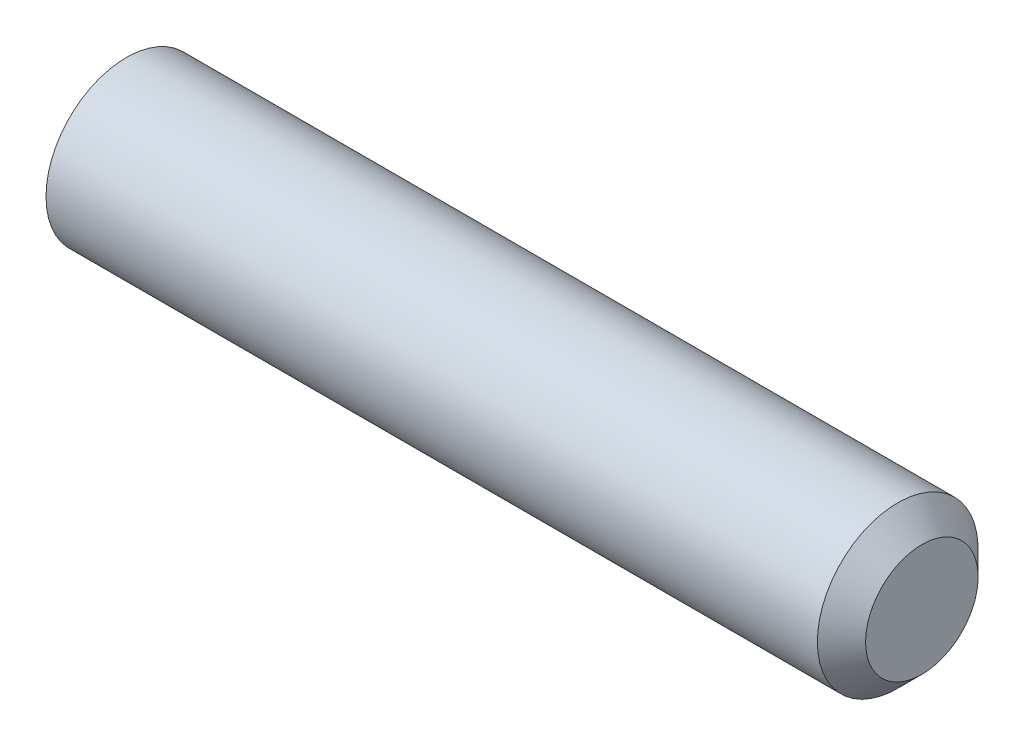
SolidWorks part; units mm, degrees
ref_plane "Plane1" through (0, 0, 0) normal (0, 0, 1) x (1, 0, 0)
ref_plane "Plane2" through (0, 0, 0) normal (0, 1, 0) x (1, 0, 0)
ref_plane "Plane3" through (0, 0, 0) normal (1, 0, 0) x (0, 0, -1)
sketch "BodySke" plane through (0, 0, 0) normal (0, 0, 1) x (1, 0, 0)
  line L0 (0, 0) -> (0, 2.055)
  line L1 (0, 2.055) -> (0.2569, 2.5)
  line L2 (0.2569, 2.5) -> (24.25, 2.5)
  line L3 (24.25, 2.5) -> (25, 1.75)
  line L4 (25, 0) -> (0, 0)
  line L5 (-12.7, 0) -> (88.9, 0) construction
  line L6 (25, 1.75) -> (25, 0)
  line L7 (25, 1.75) -> (25, 11.275) construction
  line L8 (0, -2.055) -> (0.2569, -2.5) construction
  line L9 (0.8, 15.875) -> (0.8, -3.175) construction
  line L10 (24.25, -2.5) -> (25, -1.75) construction
  dimension "Length" = 25
  dimension "Diameter" = 5
  dimension "Drive_ch_ang" = 60
  dimension "Minor_dia" = 4.11
  dimension "Cup_nose_ang" = 45
  dimension "Cup_dia" = 3.5
  dimension "Advance" = 0.8
revolve "BaseBody" add sketch "BodySke" angle 360 about L5
cosmetic thread "ThreadCosmetic" parameters "Thread_minor"=4.11
sketch "ThdSchSke" plane through (0, 0, 0) normal (0, 0, 1) x (1, 0, 0)
  line L0 (0.2569, -2.055) -> (-0.0547, -2.5)
  line L1 (0.2569, -2.055) -> (0.5685, -2.5)
  line L2 (0.5685, -2.5) -> (0.5685, -3.125)
  line L3 (-3.175, 0) -> (5.1513, 0) construction
  line L5 (0.5685, -3.125) -> (-0.0547, -3.125)
  line L6 (-0.0547, -3.125) -> (-0.0547, -2.5)
  line L8 (0.2569, 2.5) -> (0.2569, -2.5) construction
  dimension "Thread_minor" = 4.11
  dimension "Diameter" = 5
  dimension "SideAngle" = 55
  dimension "VeeAngle" = 70
  dimension "Overcut" = 6.25
revolve "ThreadSchematic" [suppressed] cut sketch "ThdSchSke" angle 360 about L3
pattern_linear "ThdSchPat" [suppressed]
equation "\"Thread_minor@ThreadCosmetic\" = \"Minor_dia@BodySke\""
equation "\"Thread_minor@ThdSchSke\" = \"Thread_minor@ThreadCosmetic\""
equation "\"Diameter@ThdSchSke\" = \"Diameter@BodySke\""
equation "\"Overcut@ThdSchSke\" = \"Diameter@BodySke\" * 1.25"
equation "\"Num_threads@ThdSchPat\" = int( (\"Length@BodySke\" - ( ( ( \"Diameter@BodySke\" - \"Minor_dia@BodySke\" ) * 0.5 ) / tan( \"Drive_ch_ang@BodySke\" * 0.017453292 ) ) - ( ( ( \"Diameter@BodySke\" - \"Cup_dia@BodySke\" ) * 0.5 ) * tan( \"Cup_nose_ang@BodySke\" * 0.017453292 ) ) ) / \"Advance@BodySke\" + 0.999 )  + 1"
equation "\"Advance@ThdSchPat\" = (\"Length@BodySke\" - ( ( ( \"Diameter@BodySke\" - \"Minor_dia@BodySke\" ) * 0.5 ) / tan( \"Drive_ch_ang@BodySke\" * 0.017453292 ) ) - ( ( ( \"Diameter@BodySke\" - \"Cup_dia@BodySke\" ) * 0.5 ) * tan( \"Cup_nose_ang@BodySke\" * 0.017453292 ) ) ) /  (\"Num_threads@ThdSchPat\" - 1) 'relax it"
equation "' \"Num_threads@ThdSchPat\" = \"Num_threads@ThdSchPat\" - sgn( \"Num_threads@ThdSchPat\" - 1) '---chamfered tips only---"
